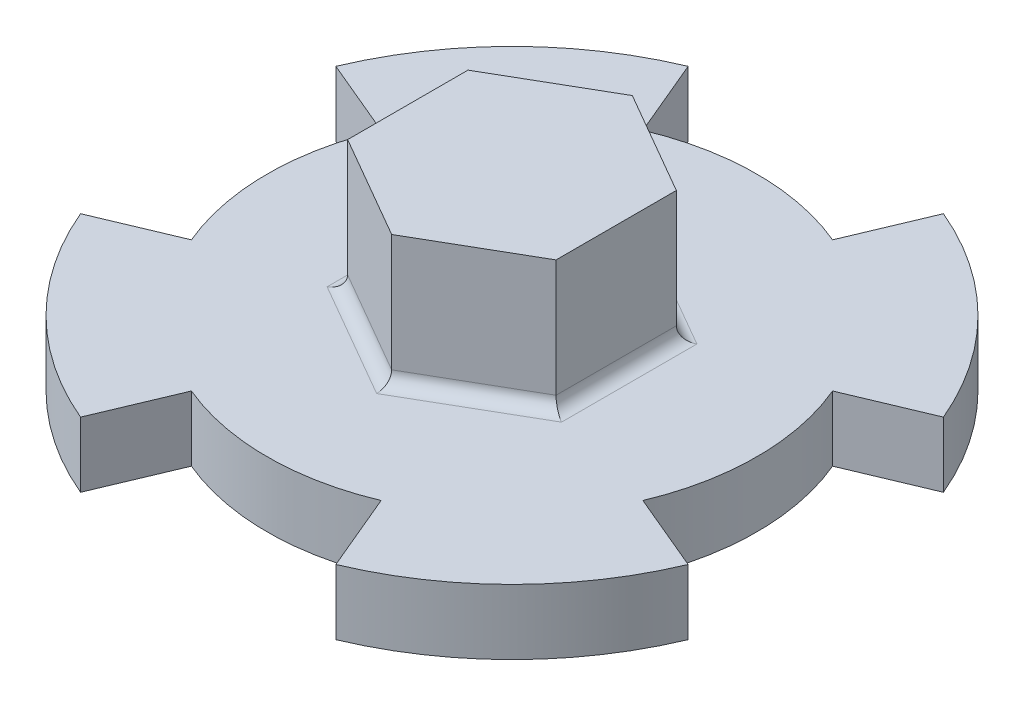
SolidWorks part; units mm, degrees
ref_plane "Front Plane" through (0, 0, 0) normal (0, 0, 1) x (1, 0, 0)
ref_plane "Top Plane" through (0, 0, 0) normal (0, 1, 0) x (1, 0, 0)
ref_plane "Right Plane" through (0, 0, 0) normal (1, 0, 0) x (0, 0, -1)
sketch "Sketch2" plane through (0, 0, 0) normal (0, 1, 0) x (1, 0, 0)
  line L0 (-7.2822, 17.3323) -> (-9.8, 23.3249)
  line L1 (0, 0) -> (0, 25.3) construction
  line L2 (7.2822, 17.3323) -> (9.8, 23.3249)
  line L3 (-17.3323, 7.2822) -> (-23.3249, 9.8)
  line L4 (-17.3323, -7.2822) -> (-23.3249, -9.8)
  line L5 (-7.2822, -17.3323) -> (-9.8, -23.3249)
  line L6 (7.2822, -17.3323) -> (9.8, -23.3249)
  line L7 (17.3323, -7.2822) -> (23.3249, -9.8)
  line L8 (17.3323, 7.2822) -> (23.3249, 9.8)
  circle A0 centre (0, 0) radius 25.3
  circle A1 centre (0, 0) radius 18.8
  circle A2 centre (0, 0) radius 25.3
  circle A3 centre (0, 0) radius 25.3
  circle A4 centre (0, 0) radius 25.3
  point P28 (0, 0)
  dimension "D1" = 50.6
  dimension "D3" = 19.6
  dimension "D4" = 9.8
  dimension "D2" = 6.5
  dimension "D5" = 4
extrude "Boss-Extrude1" add sketch "Sketch2" along normal blind 5
sketch "Sketch3" plane through (0, 5, 0) normal (0, 1, 0) x (1, 0, 0)
  line L1 (0, 9.2376) -> (-8, 4.6188)
  line L2 (-8, 4.6188) -> (-8, -4.6188)
  line L3 (-8, -4.6188) -> (0, -9.2376)
  line L4 (0, -9.2376) -> (8, -4.6188)
  line L5 (8, -4.6188) -> (8, 4.6188)
  line L6 (8, 4.6188) -> (0, 9.2376)
  circle A0 centre (0, 0) radius 8 construction
  dimension "D1" = 16
extrude "Boss-Extrude2" add sketch "Sketch3" along normal blind 10
fillet "Fillet3" radius 1 6 edges at (4, 5, 6.9282) (-4, 5, 6.9282) (-8, 5, 0) (-4, 5, -6.9282) (4, 5, -6.9282) (8, 5, 0)
